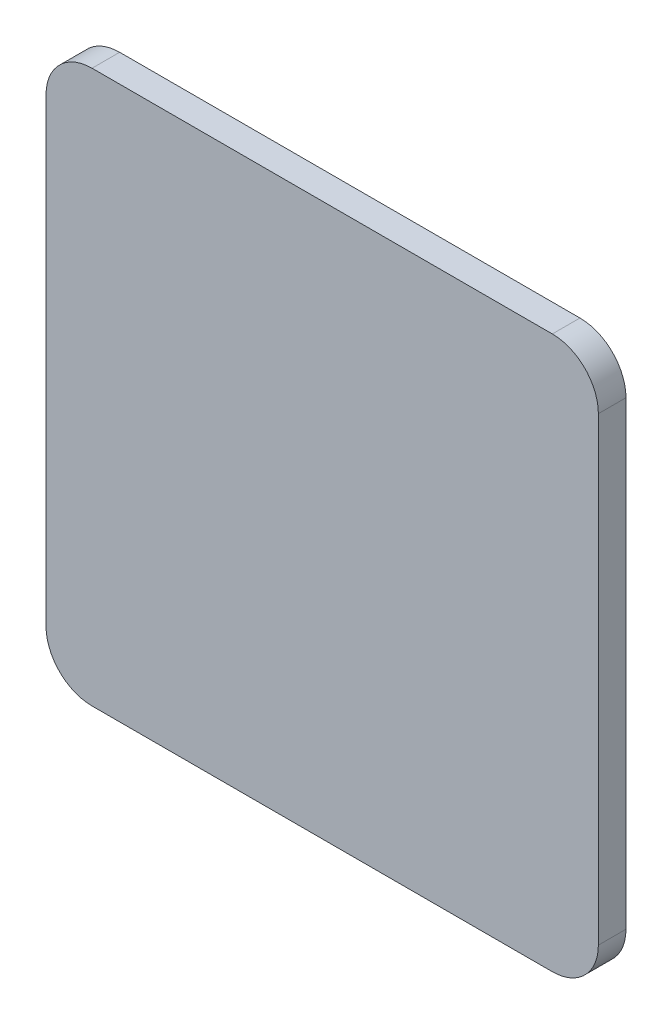
SolidWorks part; units mm, degrees
material "AISI 304"
ref_plane "Спереди" through (0, 0, 0) normal (0, 0, 1) x (1, 0, 0)
ref_plane "Сверху" through (0, 0, 0) normal (0, 1, 0) x (1, 0, 0)
ref_plane "Справа" through (0, 0, 0) normal (1, 0, 0) x (0, 0, -1)
other "Configuration Table"
sketch "Эскиз2" plane through (0, 0, 0) normal (0, 0, 1) x (1, 0, 0)
  line L1 (-30, -30) -> (30, -30)
  line L2 (-30, -30) -> (-30, 30)
  line L3 (-30, 30) -> (30, 30)
  line L4 (30, -30) -> (30, 30)
  line L5 (-30, -30) -> (30, 30) construction
  line L6 (-30, 30) -> (30, -30) construction
  point P0 (0, 0)
  dimension "D1" = 60
extrude "Бобышка-Вытянуть1" add sketch "Эскиз2" along normal mid plane 3
fillet "Скругление1" radius 5 4 edges at (-30, 30, 0) (-30, -30, 0) (30, -30, 0) (30, 30, 0)
